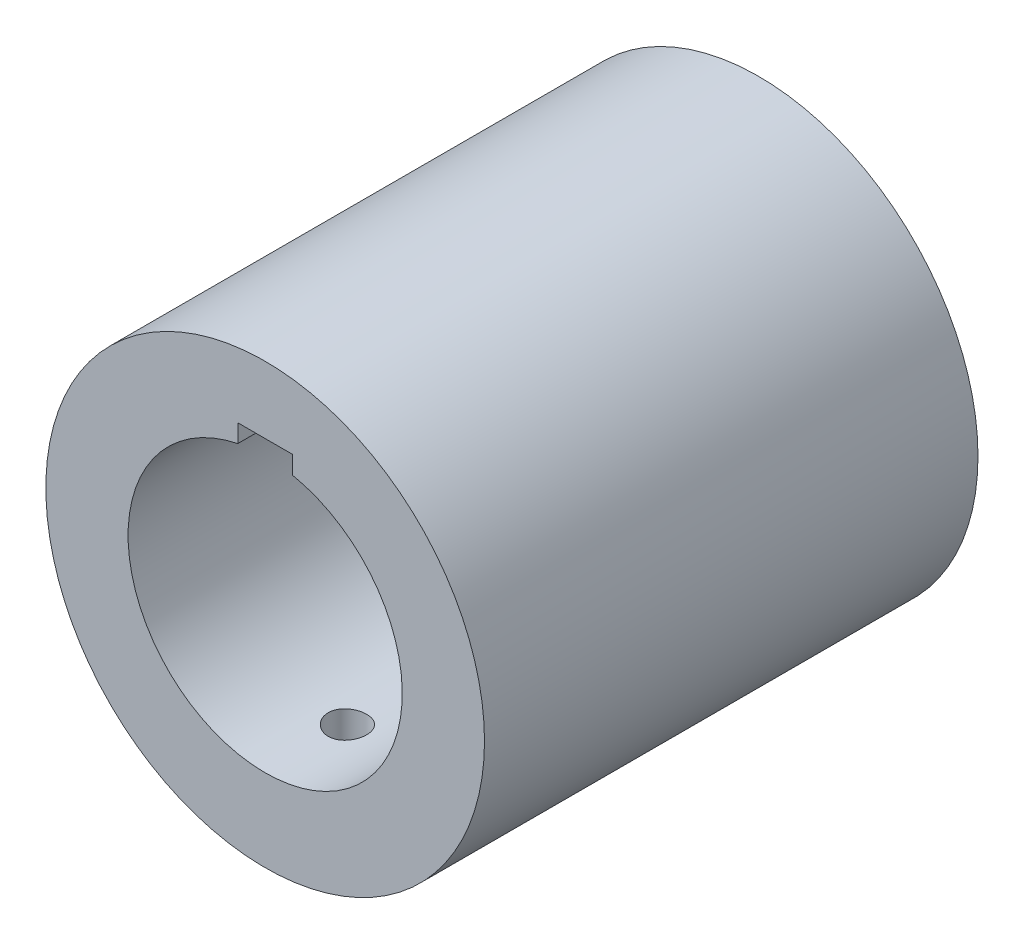
SolidWorks part; units mm, degrees
material "CK45"
ref_plane "Front Plane" through (0, 0, 0) normal (0, 0, 1) x (1, 0, 0)
ref_plane "Top Plane" through (0, 0, 0) normal (0, 1, 0) x (1, 0, 0)
ref_plane "Right Plane" through (0, 0, 0) normal (1, 0, 0) x (0, 0, -1)
sketch "Sketch1" plane through (0, 0, 0) normal (0, 0, 1) x (1, 0, 0)
  circle A0 centre (0, 0) radius 40
  dimension "D1" = 80
extrude "Boss-Extrude1" add sketch "Sketch1" along normal mid plane 90
sketch "Sketch2" plane through (0, 0, 45) normal (0, 0, 1) x (1, 0, 0)
  circle A0 centre (0, 0) radius 25
  dimension "D1" = 50
extrude "Cut-Extrude1" cut sketch "Sketch2" against normal blind 50
sketch "Sketch3" plane through (0, 0, -45) normal (0, 0, -1) x (-1, 0, 0)
  line L1 (-22.5, -22.5) -> (22.5, -22.5)
  line L2 (-22.5, -22.5) -> (-22.5, 22.5)
  line L3 (-22.5, 22.5) -> (22.5, 22.5)
  line L4 (22.5, -22.5) -> (22.5, 22.5)
  line L5 (-22.5, -22.5) -> (22.5, 22.5) construction
  line L6 (-22.5, 22.5) -> (22.5, -22.5) construction
  point P0 (0, 0)
  dimension "D1" = 45
extrude "Cut-Extrude2" cut sketch "Sketch3" against normal blind 40
sketch "Sketch4" plane through (0, 0, 45) normal (0, 0, 1) x (1, 0, 0)
  line L0 (0, 0) -> (0, 26.5043) construction
  line L2 (5, 15.79) -> (-5, 15.79)
  line L3 (5, 15.79) -> (5, 27.79)
  line L4 (5, 27.79) -> (-5, 27.79)
  line L5 (-5, 15.79) -> (-5, 27.79)
  line L6 (5, 15.79) -> (-5, 27.79) construction
  line L7 (5, 27.79) -> (-5, 15.79) construction
  point P3 (0, 21.79)
  dimension "D1" = 10
  dimension "D2" = 27.79
  dimension "D3" = 12
extrude "Cut-Extrude3" cut sketch "Sketch4" against normal blind 40
ref_plane "Plane1" through (0, -40, 45) normal (0, -1, 0) x (-1, 0, 0)
sketch "Sketch5" plane through (0, -40, 45) normal (0, -1, 0) x (-1, 0, 0)
  line L0 (40, 90) -> (-40, 90) construction
  line L1 (-40, 0) -> (40, 0) construction
  circle A0 centre (0, 15) radius 3.5
  circle A1 centre (0, 75) radius 3.5
  dimension "D2" = 15
  dimension "D3" = 7
  dimension "D1" = 15
extrude "Cut-Extrude4" cut sketch "Sketch5" against normal blind 30
